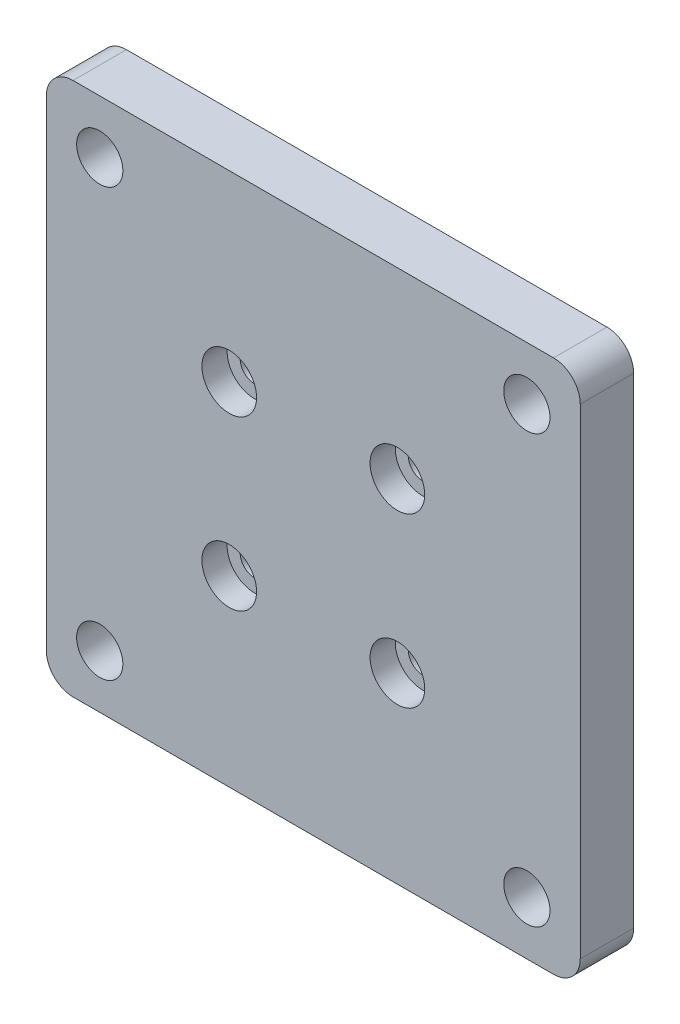
SolidWorks part; units mm, degrees
material "PETG"
ref_plane "Front Plane" through (0, 0, 0) normal (0, 0, 1) x (1, 0, 0)
ref_plane "Top Plane" through (0, 0, 0) normal (0, 1, 0) x (1, 0, 0)
ref_plane "Right Plane" through (0, 0, 0) normal (1, 0, 0) x (0, 0, -1)
sketch "Sketch1" plane through (0, 0, 0) normal (0, 0, 1) x (1, 0, 0)
  line L1 (31.75, -31.75) -> (-31.75, -31.75)
  line L2 (31.75, -31.75) -> (31.75, 31.75)
  line L3 (31.75, 31.75) -> (-31.75, 31.75)
  line L4 (-31.75, -31.75) -> (-31.75, 31.75)
  line L5 (31.75, -31.75) -> (-31.75, 31.75) construction
  line L6 (31.75, 31.75) -> (-31.75, -31.75) construction
  point P0 (0, 0)
  dimension "D1" = 63.5
  dimension "2.50" = 63.5
extrude "Boss-Extrude1" add sketch "Sketch1" along normal mid plane 6.35
sketch "Sketch2" plane through (0, 0, 3.175) normal (0, 0, 1) x (1, 0, 0)
  line L1 (-10, -10) -> (10, -10) construction
  line L2 (-10, -10) -> (-10, 10) construction
  line L3 (-10, 10) -> (10, 10) construction
  line L4 (10, -10) -> (10, 10) construction
  line L5 (-10, -10) -> (10, 10) construction
  line L6 (-10, 10) -> (10, -10) construction
  line L7 (-31.75, -31.75) -> (31.75, -31.75) construction
  point P0 (0, 0)
  point P1 (10, 10)
  point P2 (-10, -10)
  point P3 (-10, 10)
  point P4 (10, -10)
  point P7 (-10, 10)
  point P8 (10, 10)
  point P9 (10, -10)
  point P10 (-10, -10)
  dimension "D1" = 20
  dimension "D2" = 20
  dimension "D3" = 31.75
hole_wizard "CBORE for M3 SHCS1" positions "Sketch2" profile "Sketch3" counterbore size "M3" standard "ANSI Metric"
sketch "Sketch3" plane through (-10, -10, 3.175) normal (1, 0, 0) x (0, -1, 0)
  line L0 (0, 0) -> (0, 6.35)
  line L1 (0, 6.35) -> (1.7, 6.35)
  line L3 (1.7, 6.35) -> (1.7, 3)
  line L4 (1.7, 3) -> (3.25, 3)
  line L5 (3.25, 3) -> (3.25, 0)
  line L7 (3.25, 0) -> (0, 0)
  line L11 (0, -6.35) -> (0, 107.95) construction
  dimension "Thru Hole Dia." = 3.4
  dimension "Thru Hole Depth" = 6.35
  dimension "C'Bore Dia." = 6.5
  dimension "C'Bore Depth" = 3
sketch "Sketch11" plane through (0, 0, 3.175) normal (0, 0, 1) x (1, 0, 0)
  line L1 (25.4, -25.4) -> (-25.4, -25.4)
  line L2 (25.4, -25.4) -> (25.4, 25.4)
  line L3 (25.4, 25.4) -> (-25.4, 25.4)
  line L4 (-25.4, -25.4) -> (-25.4, 25.4)
  line L5 (25.4, -25.4) -> (-25.4, 25.4) construction
  line L6 (25.4, 25.4) -> (-25.4, -25.4) construction
  line L7 (-31.75, -31.75) -> (31.75, -31.75) construction
  point P0 (0, 0)
  point P1 (-25.4, 25.4)
  point P2 (25.4, -25.4)
  point P3 (25.4, 25.4)
  point P4 (-25.4, -25.4)
  dimension "D1" = 50.8
  dimension "D2" = 50.8
  dimension "D3" = 6.35
hole_wizard "M5 Clearance Hole1" positions "Sketch11" profile "Sketch12" hole size "M5" standard "ANSI Metric"
sketch "Sketch12" plane through (-25.4, -25.4, 3.175) normal (1, 0, 0) x (0, -1, 0)
  line L0 (0, 0) -> (0, 6.35)
  line L1 (0, 6.35) -> (2.75, 6.35)
  line L2 (2.75, 6.35) -> (2.75, 0)
  line L5 (2.75, 0) -> (0, 0)
  line L11 (0, -6.35) -> (0, 107.95) construction
  dimension "Thru Hole Dia." = 5.5
  dimension "Thru Hole Depth" = 6.35
fillet "Fillet1" radius 3.175 4 edges at (31.75, -31.75, 0) (-31.75, -31.75, 0) (-31.75, 31.75, 0) (31.75, 31.75, 0)
